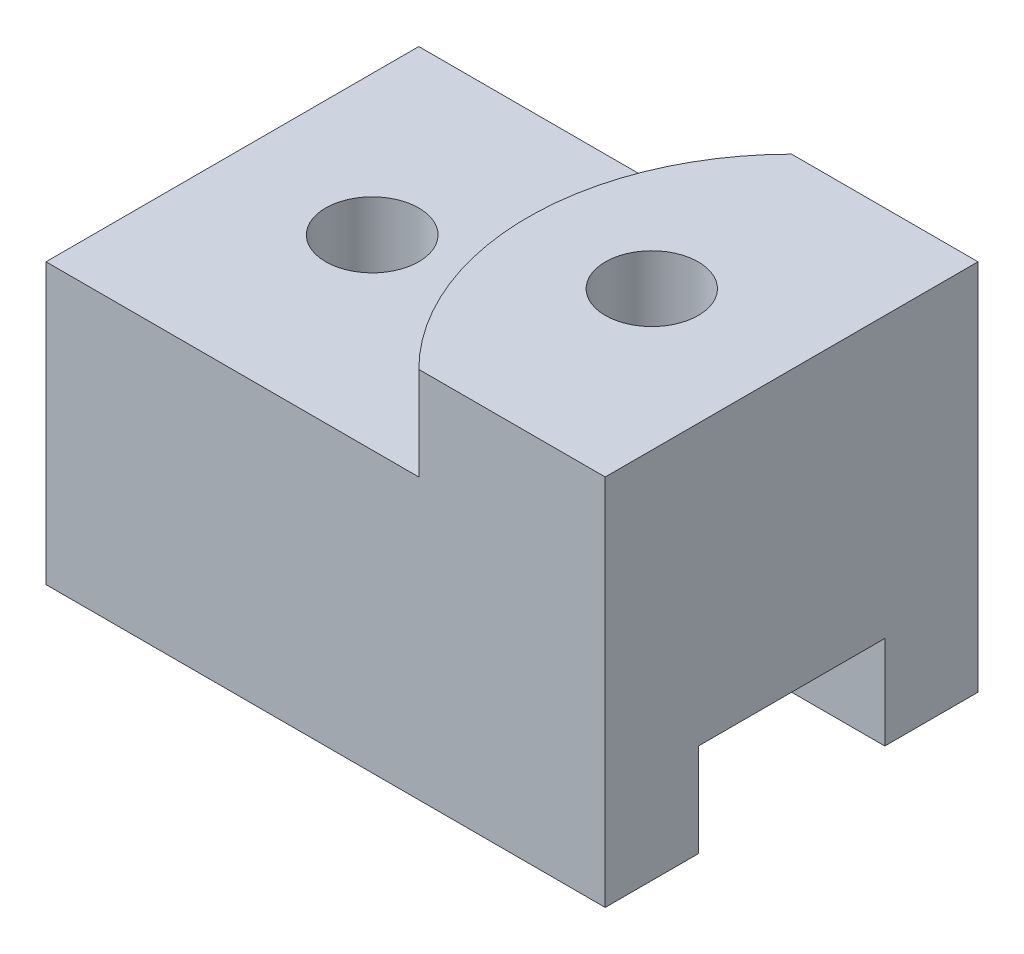
SolidWorks part; units mm, degrees
ref_plane "Front Plane" through (0, 0, 0) normal (0, 0, 1) x (1, 0, 0)
ref_plane "Top Plane" through (0, 0, 0) normal (0, 1, 0) x (1, 0, 0)
ref_plane "Right Plane" through (0, 0, 0) normal (1, 0, 0) x (0, 0, -1)
sketch "Sketch1" plane through (0, 0, 0) normal (0, 1, 0) x (1, 0, 0)
  line L0 (0, 0) -> (0, 101.6)
  line L1 (0, 101.6) -> (152.4, 101.6)
  line L2 (152.4, 101.6) -> (152.4, 0)
  line L3 (152.4, 0) -> (0, 0)
  dimension "D1" = 152.4
  dimension "D2" = 101.6
extrude "Boss-Extrude1" add sketch "Sketch1" along normal blind 101.6 contours L1 L2 L3 L0
sketch "Sketch2" plane through (0, 0, 0) normal (0, -1, 0) x (-1, 0, 0)
  line L1 (0, 0) -> (0, 101.6) construction
  line L2 (0, 25.4) -> (-152.4, 25.4)
  line L3 (-152.4, 101.6) -> (-152.4, 0) construction
  line L6 (0, 101.6) -> (-152.4, 101.6) construction
  line L7 (0, 76.2) -> (-152.4, 76.2)
  line L9 (0, 25.4) -> (0, 76.2)
  line L10 (-152.4, 76.2) -> (-152.4, 25.4)
  dimension "D1" = 25.4
  dimension "D2" = 76.2
extrude "Cut-Extrude1" cut sketch "Sketch2" against normal blind 25.4
sketch "Sketch3" plane through (0, 101.6, 0) normal (0, 1, 0) x (1, 0, 0)
  line L0 (0, 0) -> (76.2, 0)
  line L1 (152.4, 0) -> (0, 0) construction
  line L2 (76.2, 0) -> (76.2, 101.6)
  line L3 (0, 101.6) -> (152.4, 101.6) construction
  line L4 (76.2, 101.6) -> (0, 101.6)
  line L5 (0, 101.6) -> (0, 0)
extrude "Cut-Extrude2" cut sketch "Sketch3" against normal blind 25.4
sketch "Sketch4" plane through (0, 101.6, 0) normal (0, 1, 0) x (1, 0, 0)
  line L0 (152.4, 0) -> (76.2, 0)
  line L1 (76.2, 0) -> (76.2, 101.6)
  line L2 (76.2, 101.6) -> (152.4, 101.6)
  line L3 (152.4, 101.6) -> (152.4, 0)
extrude "Cut-Extrude3" cut sketch "Sketch4" against normal blind 25.4
sketch "Sketch5" plane through (0, 76.2, 0) normal (0, 1, 0) x (1, 0, 0)
  line L0 (152.4, 0) -> (101.6, 0)
  line L1 (0, 0) -> (152.4, 0) construction
  line L2 (152.4, 101.6) -> (101.6, 101.6)
  line L3 (152.4, 101.6) -> (0, 101.6) construction
  line L4 (152.4, 101.6) -> (152.4, 0)
  arc A0 (101.6, 0) -> (101.6, 101.6) centre (152.4, 50.8) cw
  dimension "D1" = 71.842
extrude "Boss-Extrude2" add sketch "Sketch5" along normal blind 25.4 contours L4 L0 A0 L2
sketch "Sketch6" plane through (0, 101.6, 0) normal (0, 1, 0) x (1, 0, 0)
  line L0 (152.4, 101.6) -> (101.6, 101.6) construction
  circle A0 centre (114.3, 50.8) radius 12.6652
  dimension "D1" = 25.3303
  dimension "D2" = 12.7
  dimension "D3" = 50.8
extrude "Cut-Extrude6" cut sketch "Sketch6" against normal blind 101.6
sketch "Sketch7" plane through (0, 76.2, 0) normal (0, 1, 0) x (1, 0, 0)
  circle A0 centre (38.1, 50.8) radius 12.7
extrude "Cut-Extrude7" cut sketch "Sketch7" against normal blind 50.8
sketch "Sketch8" plane through (0, 25.4, 0) normal (0, -1, 0) x (1, 0, 0)
  circle A0 centre (38.1, -50.8) radius 19.05
  dimension "D1" = 38.1
extrude "Cut-Extrude8" cut sketch "Sketch8" against normal blind 8.382
